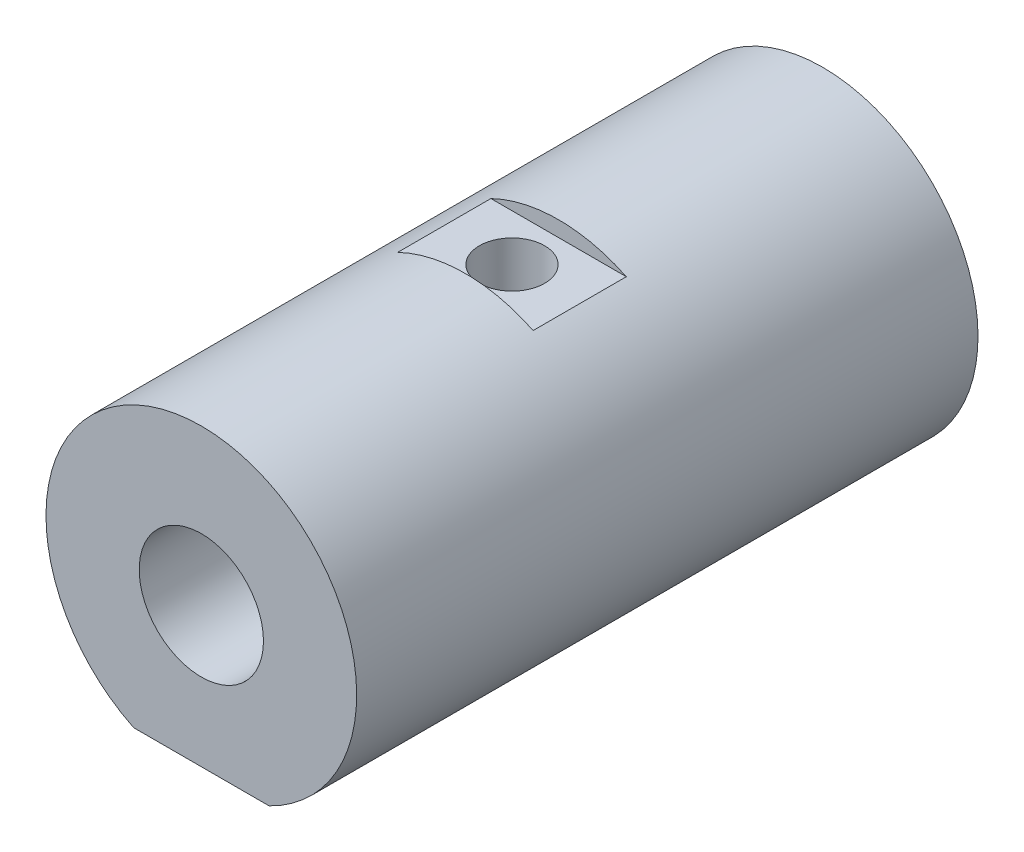
SolidWorks part; units mm, degrees
ref_plane "Front Plane" through (0, 0, 0) normal (0, 0, 1) x (1, 0, 0)
ref_plane "Top Plane" through (0, 0, 0) normal (0, 1, 0) x (1, 0, 0)
ref_plane "Right Plane" through (0, 0, 0) normal (1, 0, 0) x (0, 0, -1)
sketch "Sketch1" plane through (0, 0, 0) normal (0, 0, 1) x (1, 0, 0)
  circle A0 centre (0, 0) radius 4
  circle A1 centre (0, 0) radius 10
  dimension "D1" = 8
  dimension "D2" = 20
extrude "Boss-Extrude1" add sketch "Sketch1" along normal blind 40
hole_wizard "Ø4.2 (4.2) Diameter Hole2" positions "Sketch3" profile "Sketch4" hole size "Ø4.2" standard "DIN"
sketch "Sketch3" plane through (0, 0, 0) normal (0, 1, 0) x (1, 0, 0)
  line L0 (0, 0) -> (0, -40) construction
  line L1 (4, 0) -> (-4, 0) construction
  line L2 (-10, -40) -> (10, -40) construction
  point P9 (0, -20)
sketch "Sketch4" plane through (0, 0, 20) normal (1, 0, 0) x (0, 0, -1)
  line L0 (0, 0) -> (0, 10)
  line L1 (0, 10) -> (2.1, 10)
  line L2 (2.1, 10) -> (2.1, 0)
  line L5 (2.1, 0) -> (0, 0)
  line L11 (0, -6.35) -> (0, 107.95) construction
  dimension "Thru Hole Dia." = 4.2
  dimension "Thru Hole Depth" = 10
sketch "Sketch5" plane through (0, 0, 0) normal (0, 1, 0) x (1, 0, 0)
  line L0 (10, -40) -> (10, 0) construction
  line L1 (-10, -23) -> (10, -23)
  line L2 (-10, -23) -> (-10, -17)
  line L3 (-10, -17) -> (10, -17)
  line L4 (10, -23) -> (10, -17)
  line L5 (-10, -23) -> (10, -17) construction
  line L6 (-10, -17) -> (10, -23) construction
  point P0 (0, -20)
  dimension "D1" = 6
extrude "Cut-Extrude1" cut sketch "Sketch5" against normal blind 1 from offset 10
hole_wizard "Ø4.2 (4.2) Diameter Hole1" positions "Sketch6" profile "Sketch7" hole size "Ø4.2" standard "DIN"
sketch "Sketch6" plane through (0, 0, 0) normal (0, 1, 0) x (1, 0, 0)
  line L0 (0, 0) -> (0, -40) construction
  line L1 (4, 0) -> (-4, 0) construction
  line L2 (-10, -40) -> (10, -40) construction
  point P9 (0, -20)
  point P14 (0, -10)
  point P16 (0, -30)
  dimension "D1" = 10
  dimension "D2" = 10
sketch "Sketch7" plane through (0, 0, 30) normal (1, 0, 0) x (0, 0, 1)
  line L0 (0, 0) -> (0, 10)
  line L1 (0, 10) -> (2.1, 10)
  line L2 (2.1, 10) -> (2.1, 0)
  line L5 (2.1, 0) -> (0, 0)
  line L11 (0, -6.35) -> (0, 107.95) construction
  dimension "Thru Hole Dia." = 4.2
  dimension "Thru Hole Depth" = 10
sketch "Sketch8" plane through (0, 0, 0) normal (0, 1, 0) x (1, 0, 0)
  line L0 (-10, -40) -> (10, -40) construction
  line L1 (10, -40) -> (10, 0) construction
  line L2 (10, 0) -> (-10, 0) construction
  line L3 (-10, 0) -> (-10, -40) construction
  line L4 (-10, -40) -> (10, -40)
  line L5 (10, -40) -> (10, 0)
  line L6 (10, 0) -> (-10, 0)
  line L7 (-10, 0) -> (-10, -40)
extrude "Cut-Extrude3" cut sketch "Sketch8" along normal blind 1 from offset 10 offset against normal yes
equation "\"D2@Sketch6\"=\"D1@Sketch6\""
